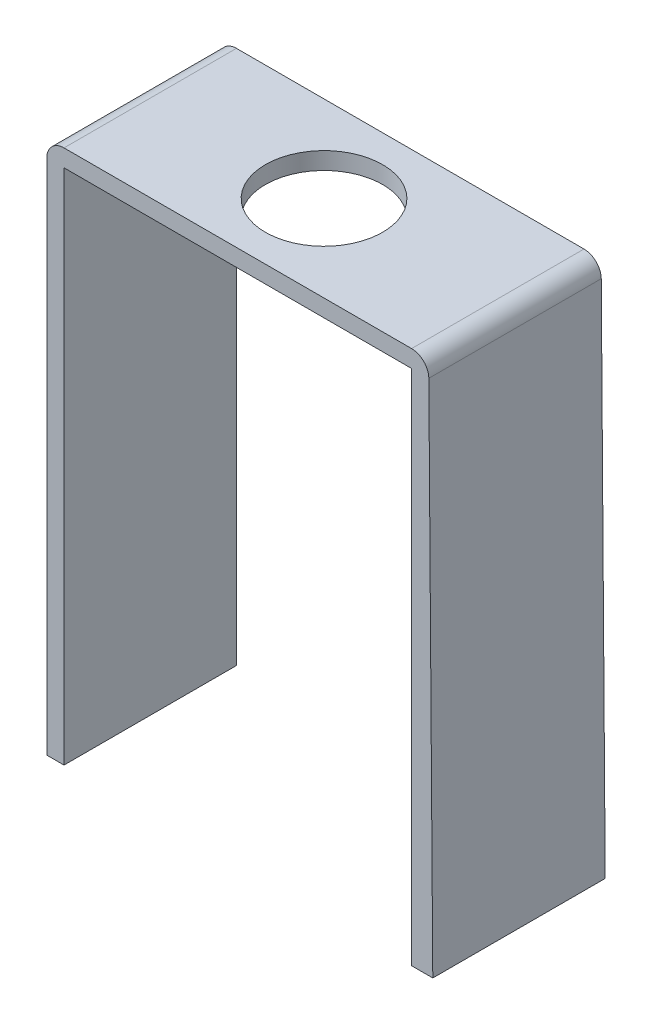
SolidWorks part; units mm, degrees
ref_plane "前视基准面" through (0, 0, 0) normal (0, 0, 1) x (1, 0, 0)
ref_plane "上视基准面" through (0, 0, 0) normal (0, 1, 0) x (1, 0, 0)
ref_plane "右视基准面" through (0, 0, 0) normal (1, 0, 0) x (0, 0, -1)
other "Configuration Table"
sketch "草图1" plane through (0, 0, 0) normal (0, 0, 1) x (1, 0, 0)
  line L0 (-27.3514, 53.2892) -> (-27.3514, -8.7108)
  line L5 (-27.3514, -8.7108) -> (-25.3514, -8.7108)
  line L6 (-25.3514, -8.7108) -> (-25.3514, 51.2892)
  line L7 (-25.3514, 51.2892) -> (14.9486, 51.2892)
  line L8 (14.9486, 51.2892) -> (14.9486, -8.7108)
  line L9 (14.9486, -8.7108) -> (17.4231, -8.7108)
  line L10 (17.4231, -8.7108) -> (16.9486, 53.2892)
  line L11 (16.9486, 53.2892) -> (-27.3514, 53.2892)
  dimension "D1" = 62
  dimension "D2" = 62
  dimension "D3" = 44.3
  dimension "D4" = 2
  dimension "D5" = 2
  dimension "D6" = 40.3
  dimension "D7" = 0.438
extrude "凸台-拉伸1" add sketch "草图1" along normal blind 20
fillet "圆角2" radius 2 1 edges at (-27.3514, 53.2892, 10)
fillet "圆角4" radius 2 1 edges at (16.9486, 53.2892, 10)
sketch "草图2" plane through (0, 53.2892, 0) normal (0, 1, 0) x (1, 0, 0)
  line L0 (-5.1938, -10) -> (-29.0191, -10) construction
  line L1 (-29.0191, -10) -> (21.0499, -10) construction
  line L2 (21.0499, -10) -> (-5.1938, -10) construction
  line L3 (-5.1938, -10) -> (-5.1938, 6.1749) construction
  circle A0 centre (-5.1938, -10) radius 6.8
  dimension "D1" = 13.6
extrude "切除-拉伸2" cut sketch "草图2" against normal blind 20
